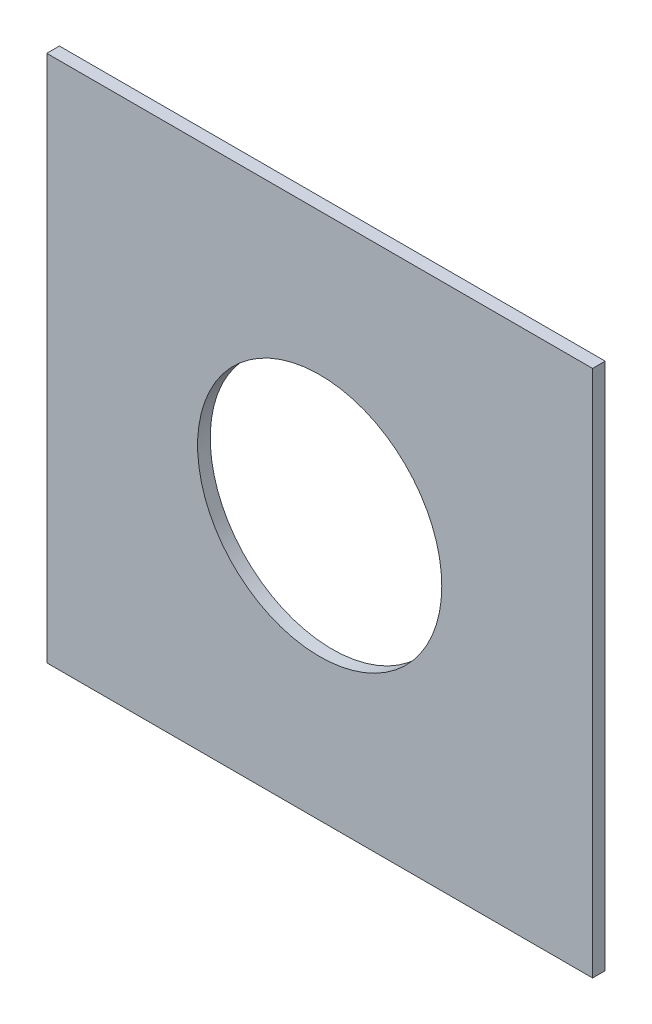
SolidWorks part; units mm, degrees
ref_plane "Front Plane" through (0, 0, 0) normal (0, 0, 1) x (1, 0, 0)
ref_plane "Top Plane" through (0, 0, 0) normal (0, 1, 0) x (1, 0, 0)
ref_plane "Right Plane" through (0, 0, 0) normal (1, 0, 0) x (0, 0, -1)
sketch "Sketch1" plane through (0, 0, 0) normal (0, 0, 1) x (1, 0, 0)
  line L1 (-120.65, -116.688) -> (120.65, -116.688)
  line L2 (-120.65, -116.688) -> (-120.65, 116.688)
  line L3 (-120.65, 116.688) -> (120.65, 116.688)
  line L4 (120.65, -116.688) -> (120.65, 116.688)
  line L5 (-120.65, -116.688) -> (120.65, 116.688) construction
  line L6 (-120.65, 116.688) -> (120.65, -116.688) construction
  point P0 (0, 0)
  dimension "D1" = 241.3
  dimension "D2" = 233.376
extrude "Boss-Extrude1" add sketch "Sketch1" along normal blind 5.588
sketch "Sketch2" plane through (0, 0, 5.588) normal (0, 0, 1) x (1, 0, 0)
  circle A1 centre (0, 0) radius 53.975
  point P2 (0, 0)
  point P3 (0, 0)
  dimension "D2" = 107.95
extrude "Cut-Extrude1" cut sketch "Sketch2" against normal through all
sketch "Sketch3" plane through (0, 0, 5.588) normal (0, 0, 1) x (1, 0, 0)
  line L0 (-115.57, 116.688) -> (-115.57, -116.688) construction
  line L1 (120.65, 116.688) -> (-120.65, 116.688) construction
  line L2 (-120.65, -116.688) -> (120.65, -116.688) construction
  line L3 (-120.65, 116.688) -> (-120.65, -116.688) construction
  line L4 (0, 0) -> (-102.87, 0) construction
  line L5 (-115.57, 19.05) -> (-102.87, 19.05)
  line L6 (-115.57, 19.05) -> (-115.57, -19.05)
  line L7 (-115.57, -19.05) -> (-102.87, -19.05)
  line L8 (-102.87, 19.05) -> (-102.87, -19.05)
  line L9 (0, 116.688) -> (0, -116.688) construction
  line L10 (115.57, -19.05) -> (102.87, -19.05)
  line L11 (102.87, 19.05) -> (102.87, -19.05)
  line L12 (115.57, 19.05) -> (102.87, 19.05)
  line L13 (115.57, 19.05) -> (115.57, -19.05)
  dimension "D1" = 5.08
  dimension "D2" = 38.1
  dimension "D3" = 12.7
